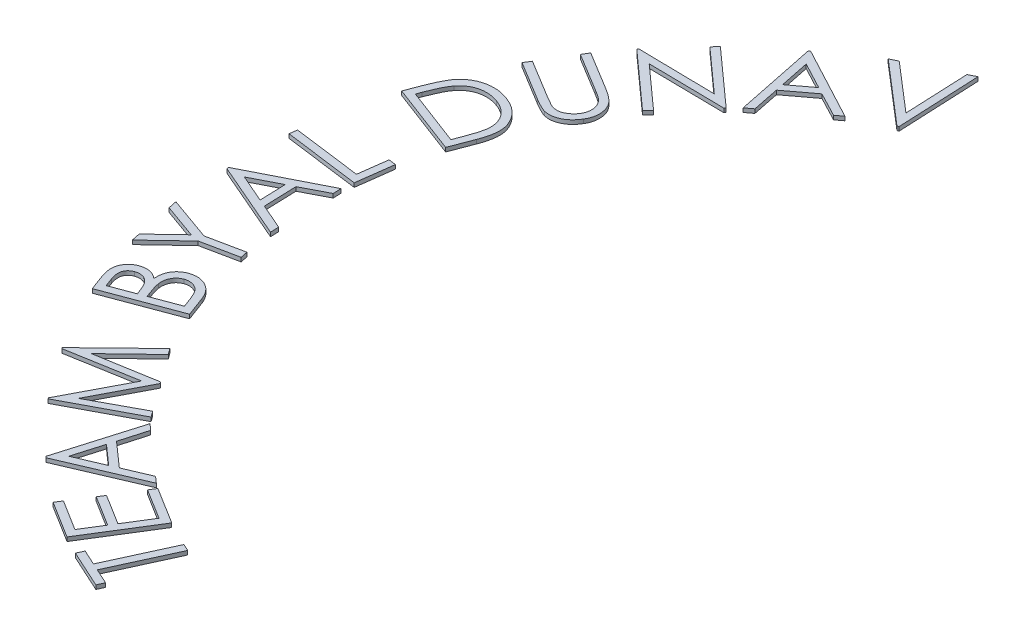
SolidWorks part; units mm, degrees
ref_plane "Front Plane" through (0, 0, 0) normal (0, 0, 1) x (1, 0, 0)
ref_plane "Top Plane" through (0, 0, 0) normal (0, 1, 0) x (1, 0, 0)
ref_plane "Right Plane" through (0, 0, 0) normal (1, 0, 0) x (0, 0, -1)
sketch "Sketch2" plane through (0, 0, 0) normal (0, 1, 0) x (1, 0, 0)
  circle A0 centre (0, 0) radius 100 construction
  text T0 "TEAM BYAL DUNAV" font "Century Gothic" height in points 72
extrude "Boss-Extrude1" add sketch "Sketch2" along normal blind 1
